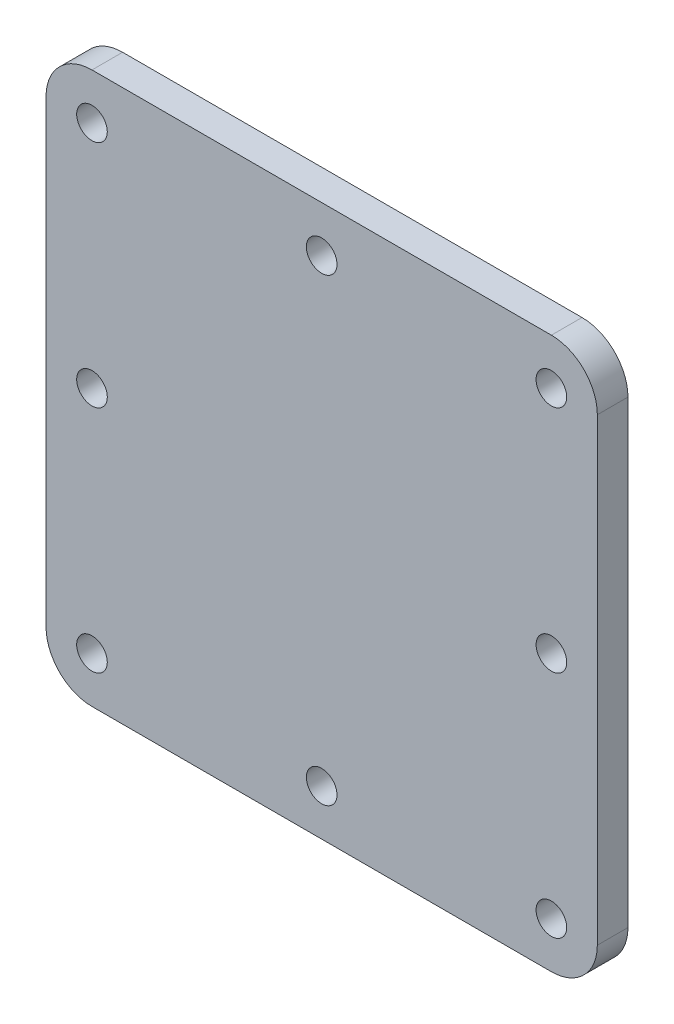
SolidWorks part; units mm, degrees
ref_plane "Front Plane" through (0, 0, 0) normal (0, 0, 1) x (1, 0, 0)
ref_plane "Top Plane" through (0, 0, 0) normal (0, 1, 0) x (1, 0, 0)
ref_plane "Right Plane" through (0, 0, 0) normal (1, 0, 0) x (0, 0, -1)
sketch "Sketch2" plane through (0, 0, 0) normal (0, 0, 1) x (1, 0, 0)
  line L0 (-75, 75) -> (75, 75) construction
  line L1 (-75, 90) -> (75, 90)
  line L2 (-90, 75) -> (-90, -75)
  line L3 (-75, -90) -> (75, -90)
  line L4 (90, 75) -> (90, -75)
  line L5 (-90, 90) -> (90, -90) construction
  line L6 (-90, -90) -> (90, 90) construction
  line L7 (75, 75) -> (75, -75) construction
  line L8 (75, -75) -> (-75, -75) construction
  line L9 (-75, -75) -> (-75, 75) construction
  line L15 (-60, 60) -> (60, -60) construction
  line L16 (-60, -60) -> (60, 60) construction
  arc A0 (-90, -75) -> (-75, -90) centre (-75, -75) ccw
  arc A1 (75, -90) -> (90, -75) centre (75, -75) ccw
  arc A2 (75, 90) -> (90, 75) centre (75, 75) cw
  arc A3 (-75, 90) -> (-90, 75) centre (-75, 75) ccw
  circle A4 centre (-75, 75) radius 5
  circle A5 centre (0, 75) radius 5
  circle A6 centre (75, 75) radius 5
  circle A7 centre (-75, 0) radius 5
  circle A8 centre (0, 0) radius 5 construction
  circle A9 centre (75, 0) radius 5
  circle A10 centre (-75, -75) radius 5
  circle A11 centre (0, -75) radius 5
  circle A12 centre (75, -75) radius 5
  point P0 (0, 0)
  dimension "D3" = 15
  dimension "D4" = 10
  dimension "D1" = 180
  dimension "D2" = 180
  dimension "D8" = 120
  dimension "D7" = 3
extrude "Boss-Extrude1" add sketch "Sketch2" along normal blind 10
